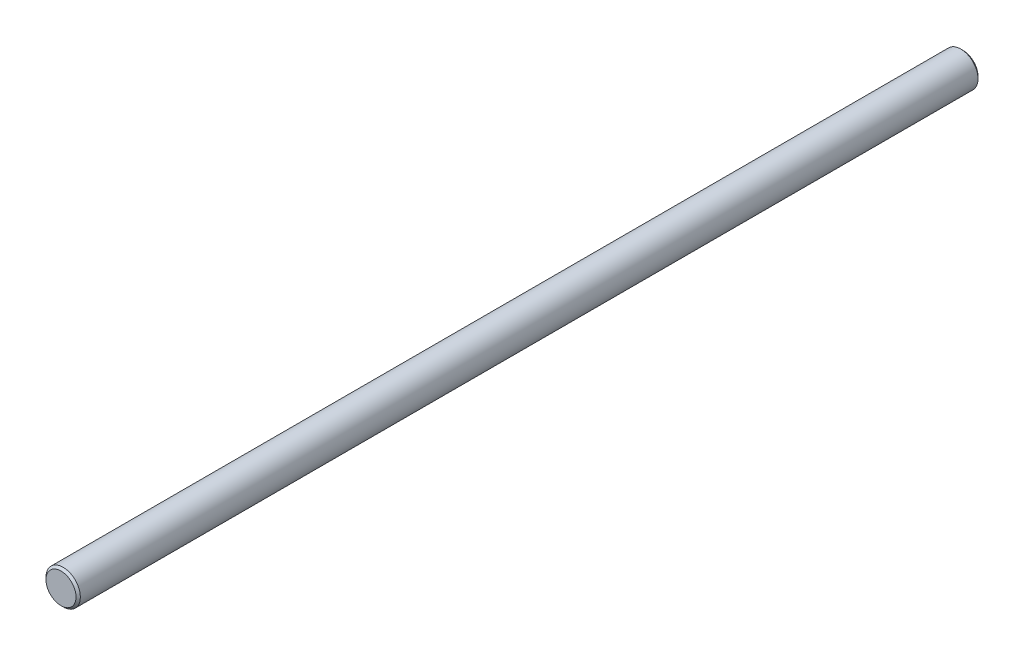
SolidWorks part; units mm, degrees
ref_plane "Front Plane" through (0, 0, 0) normal (0, 0, 1) x (1, 0, 0)
ref_plane "Top Plane" through (0, 0, 0) normal (0, 1, 0) x (1, 0, 0)
ref_plane "Right Plane" through (0, 0, 0) normal (1, 0, 0) x (0, 0, -1)
sketch "Sketch1" plane through (0, 0, 0) normal (0, 0, 1) x (1, 0, 0)
  circle A0 centre (0, 0) radius 8
  dimension "D1" = 16
extrude "Boss-Extrude1" add sketch "Sketch1" along normal mid plane 420
chamfer "Chamfer1" distance 1 angle 45 2 edges at (8, 0, -210) (8, 0, 210)
